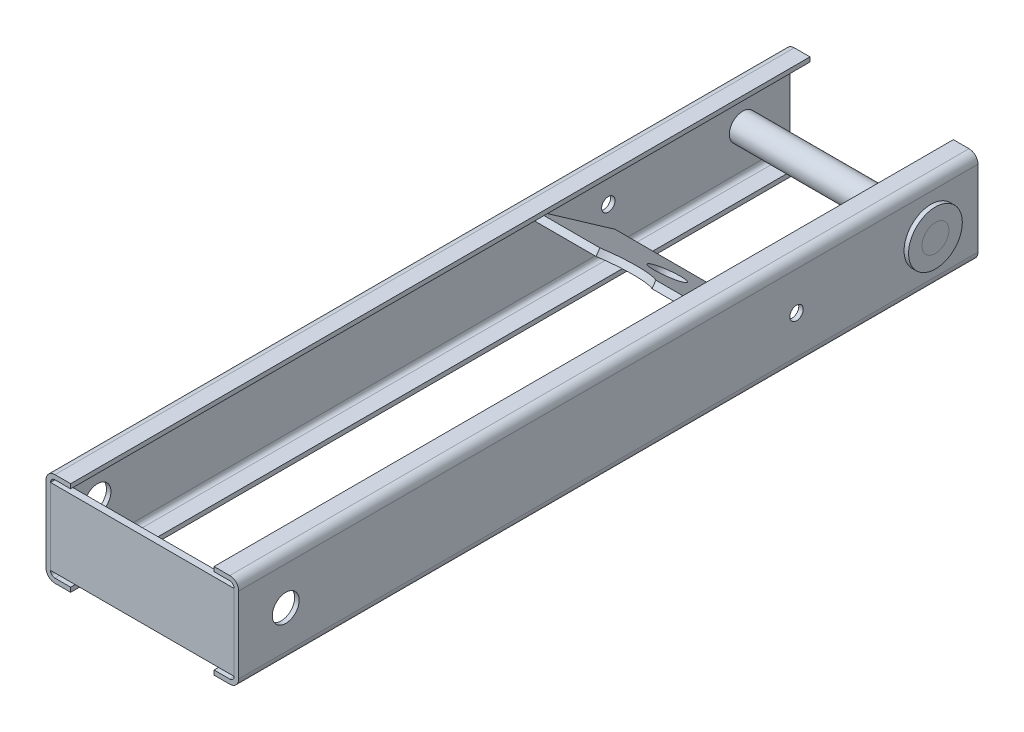
SolidWorks part; units mm, degrees
ref_plane "Спереди" through (0, 0, 0) normal (0, 0, 1) x (1, 0, 0)
ref_plane "Сверху" through (0, 0, 0) normal (0, 1, 0) x (1, 0, 0)
ref_plane "Справа" through (0, 0, 0) normal (1, 0, 0) x (0, 0, -1)
sketch "Эскиз2" plane through (0, 0, 0) normal (0, 0, 1) x (1, 0, 0)
  line L0 (43, -17) -> (43, 17)
  line L1 (39, 21) -> (32, 21)
  line L2 (39, -21) -> (32, -21)
  line L3 (39, -19) -> (32, -19)
  line L4 (41, -17) -> (41, 17)
  line L5 (39, 19) -> (32, 19)
  line L6 (32, -19) -> (32, -21)
  line L7 (32, 19) -> (32, 21)
  line L8 (0, 0) -> (0, 22.7136) construction
  line L9 (-32, 19) -> (-32, 21)
  line L10 (-32, -19) -> (-32, -21)
  line L11 (-39, 19) -> (-32, 19)
  line L12 (-41, -17) -> (-41, 17)
  line L13 (-39, -19) -> (-32, -19)
  line L14 (-39, -21) -> (-32, -21)
  line L15 (-39, 21) -> (-32, 21)
  line L16 (-43, -17) -> (-43, 17)
  arc A0 (43, 17) -> (39, 21) centre (39, 17) ccw
  arc A1 (43, -17) -> (39, -21) centre (39, -17) cw
  arc A2 (41, -17) -> (39, -19) centre (39, -17) cw
  arc A3 (41, 17) -> (39, 19) centre (39, 17) ccw
  arc A4 (-41, 17) -> (-39, 19) centre (-39, 17) cw
  arc A5 (-41, -17) -> (-39, -19) centre (-39, -17) ccw
  arc A6 (-43, -17) -> (-39, -21) centre (-39, -17) ccw
  arc A7 (-43, 17) -> (-39, 21) centre (-39, 17) cw
  point P9 (43, 21)
  point P12 (43, -21)
  dimension "D4" = 4
  dimension "D1" = 86
  dimension "D2" = 42
  dimension "D3" = 11
  dimension "D5" = 2
extrude "Бобышка-Вытянуть1" add sketch "Эскиз2" against normal blind 330
sketch "Эскиз3" plane through (-41, 0, 0) normal (1, 0, 0) x (0, 0, -1)
  line L0 (330, -17) -> (0, -17) construction
  line L1 (0, 17) -> (3, 17)
  line L2 (0, 17) -> (0, -17)
  line L3 (0, -17) -> (3, -17)
  line L4 (3, 17) -> (3, -17)
  dimension "D1" = 3
extrude "Бобышка-Вытянуть2" add sketch "Эскиз3" along normal up to next separate body
sketch "Эскиз4" plane through (-41, 0, 0) normal (1, 0, 0) x (0, 0, -1)
  line L0 (215, 11.1032) -> (250.2235, -13.5606)
  line L1 (215, 11.1032) -> (216.7207, 13.5606)
  line L2 (250.2235, -13.5606) -> (251.9443, -11.1032)
  line L3 (216.7207, 13.5606) -> (251.9443, -11.1032)
  line L4 (251.0839, -12.3319) -> (215.8604, 12.3319) construction
  line L5 (232.6118, -1.2287) -> (234.3325, 1.2287) construction
  line L6 (330, 17) -> (0, 17) construction
  line L7 (0, 17) -> (0, -17) construction
  line L8 (330, 0) -> (164.1612, 0) construction
  line L9 (330, -17) -> (330, 17) construction
  point P203 (233.4721, 0)
  dimension "D1" = 3
  dimension "D2" = 43
  dimension "D3" = 35
  dimension "D4" = 215
extrude "Бобышка-Вытянуть3" add sketch "Эскиз4" along normal up to next
sketch "Эскиз5" plane through (43, 0, 0) normal (1, 0, 0) x (0, 0, -1)
  line L0 (330, -17) -> (330, 17) construction
  line L1 (0, -17) -> (0, 17) construction
  circle A0 centre (309, 0) radius 6
  circle A1 centre (21, 0) radius 6
  circle A2 centre (249, 0) radius 3
  point P7 (330, 0)
  dimension "D1" = 12
  dimension "D4" = 6
  dimension "D2" = 15
  dimension "D3" = 15
  dimension "D5" = 78
extrude "Вырез-Вытянуть1" cut sketch "Эскиз5" against normal through all both and the other way through all
sketch "Эскиз6" plane through (0, 110.9247, -77.6703) normal (0, 0.8192, -0.5736) x (1, 0, 0)
  line L0 (41, 212.7492) -> (-41, 212.7492) construction
  line L1 (41, 169.7492) -> (41, 212.7492) construction
  line L2 (41, 169.7492) -> (-41, 169.7492) construction
  line L3 (-12.5, 169.7492) -> (12.5, 169.7492)
  circle A0 centre (0, 191.2492) radius 7
  arc A1 (-12.5, 169.7492) -> (12.5, 169.7492) centre (0, 156.6242) cw
  point P5 (0, 212.7492)
  point P8 (41, 191.2492)
  point P12 (0, 169.7492)
  dimension "D1" = 14
  dimension "D3" = 5
  dimension "D2" = 25
extrude "Вырез-Вытянуть2" cut sketch "Эскиз6" against normal up to next (3 mm away)
sketch "Эскиз7" plane through (43, 0, 0) normal (1, 0, 0) x (0, 0, -1)
  circle A0 centre (309, 0) radius 12
  circle A1 centre (309, 0) radius 6
  dimension "D1" = 24
extrude "Бобышка-Вытянуть4" add sketch "Эскиз7" along normal blind 2 separate body
sketch "Эскиз8" plane through (45, 0, 0) normal (1, 0, 0) x (0, 0, -1)
  circle A0 centre (309, 0) radius 6
extrude "Бобышка-Вытянуть5" add sketch "Эскиз8" against normal blind 90 separate body
sketch "Эскиз9" plane through (-43, 0, 0) normal (-1, 0, 0) x (0, 0, 1)
  circle A0 centre (-309, 0) radius 12
  circle A1 centre (-309, 0) radius 6
  dimension "D1" = 24
extrude "Бобышка-Вытянуть6" add sketch "Эскиз9" along normal blind 2 separate body
